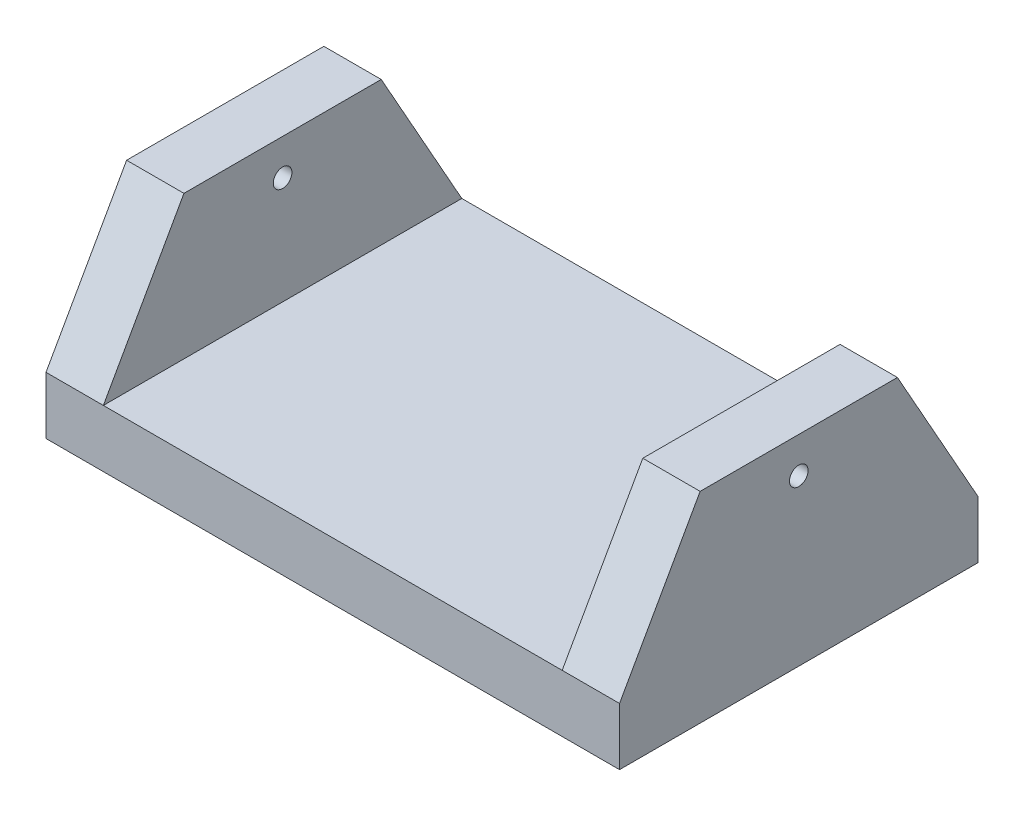
SolidWorks part; units mm, degrees
ref_plane "Front Plane" through (0, 0, 0) normal (0, 0, 1) x (1, 0, 0)
ref_plane "Top Plane" through (0, 0, 0) normal (0, 1, 0) x (1, 0, 0)
ref_plane "Right Plane" through (0, 0, 0) normal (1, 0, 0) x (0, 0, -1)
sketch "Sketch2" plane through (0, 0, 0) normal (0, 1, 0) x (1, 0, 0)
  line L1 (-40, 25) -> (40, 25)
  line L2 (-40, 25) -> (-40, -25)
  line L3 (-40, -25) -> (40, -25)
  line L4 (40, 25) -> (40, -25)
  line L5 (-40, 25) -> (40, -25) construction
  line L6 (-40, -25) -> (40, 25) construction
  point P0 (0, 0)
  dimension "D1" = 80
  dimension "D2" = 50
extrude "Boss-Extrude1" add sketch "Sketch2" along normal blind 8
sketch "Sketch3" plane through (40, 0, 0) normal (1, 0, 0) x (0, 0, -1)
  line L0 (-25, 8) -> (-13.7583, 28)
  line L1 (-13.7583, 28) -> (13.7583, 28)
  line L2 (13.7583, 28) -> (25, 8)
  line L3 (-25, 8) -> (25, 8) construction
  circle A0 centre (0, 23) radius 1.3
  line M6 (25, 8) -> (-25, 8)
  dimension "D1" = 2.6
  dimension "D2" = 20
  dimension "D3" = 5
extrude "Boss-Extrude2" add sketch "Sketch3" against normal blind 8 contours L2 L1 L0 A0 M6
mirror "Mirror1" about plane through (0, 0, 0) normal (1, 0, 0) of "Boss-Extrude2"
